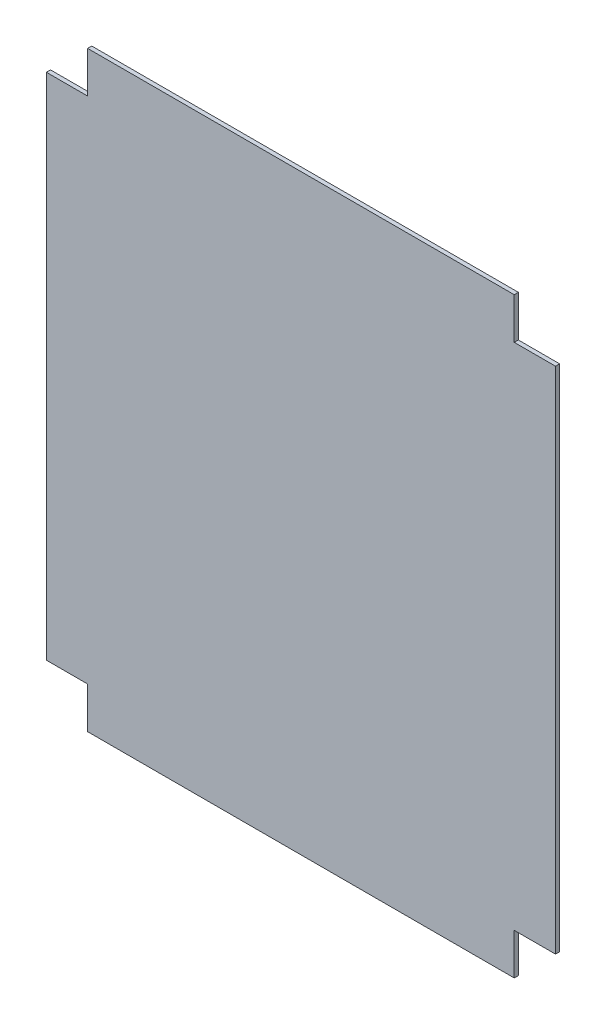
SolidWorks part; units mm, degrees
ref_plane "정면" through (0, 0, 0) normal (0, 0, 1) x (1, 0, 0)
ref_plane "윗면" through (0, 0, 0) normal (0, 1, 0) x (1, 0, 0)
ref_plane "우측면" through (0, 0, 0) normal (1, 0, 0) x (0, 0, -1)
sketch "스케치1" plane through (0, 0, 0) normal (0, 0, 1) x (1, 0, 0)
  line L0 (0, 0) -> (38.6657, 0) construction
  line L1 (-185, -215) -> (185, -215)
  line L2 (-185, -215) -> (-185, 215)
  line L3 (-185, 215) -> (185, 215)
  line L4 (185, -215) -> (185, 215)
  line L5 (-185, -215) -> (185, 215) construction
  line L6 (-185, 215) -> (185, -215) construction
  line L7 (-185, 215) -> (-155, 215)
  line L8 (-185, 215) -> (-185, 185)
  line L9 (-185, 185) -> (-155, 185)
  line L10 (-155, 215) -> (-155, 185)
  line L11 (0, 0) -> (0, 32.8997) construction
  line L12 (185, 185) -> (155, 185)
  line L13 (155, 215) -> (155, 185)
  line L14 (185, -185) -> (155, -185)
  line L15 (155, -215) -> (155, -185)
  line L16 (-155, -215) -> (-155, -185)
  line L17 (-185, -185) -> (-155, -185)
  point P0 (0, 0)
  dimension "D1" = 370
  dimension "D2" = 430
  dimension "D3" = 30
  dimension "D4" = 30
extrude "보스-돌출1" add sketch "스케치1" along normal blind 3 contours L2 L17 L16 L1 L15 L14 L4 L12 L13 L3 L10 L9
